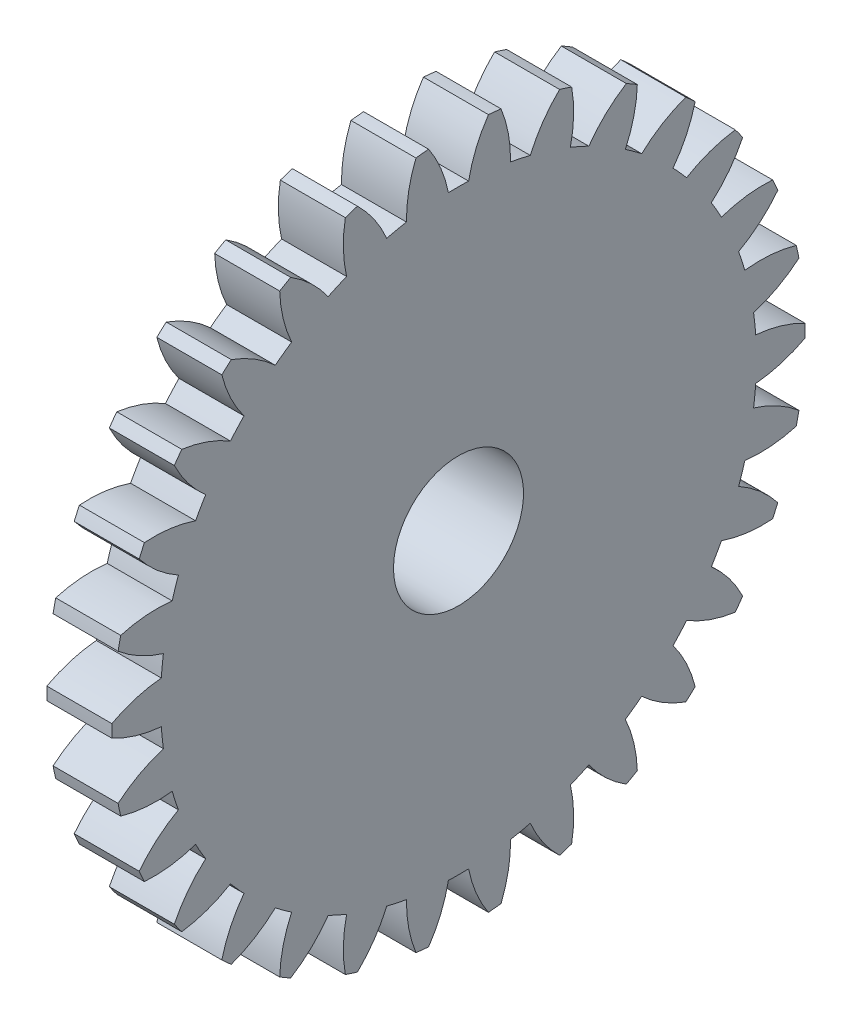
SolidWorks part; units mm, degrees
ref_plane "Plane1" through (0, 0, 0) normal (0, 0, 1) x (1, 0, 0)
ref_plane "Plane2" through (0, 0, 0) normal (0, 1, 0) x (1, 0, 0)
ref_plane "Plane3" through (0, 0, 0) normal (1, 0, 0) x (0, 0, -1)
sketch "HoldingSke" plane through (0, 0, 0) normal (0, 1, 0) x (1, 0, 0)
  line L0 (0, 0) -> (0.866, -0.5)
  line L1 (-15, 0) -> (100, 0) construction
  line L2 (0, 0) -> (-2.1039, 2.3779)
  line L3 (0, 0) -> (-11.863, 4.5341)
  line L4 (0, 0) -> (7.479, 4.318)
  line L5 (0, 0) -> (-5.6217, -2.0967)
  line L6 (0, 0) -> (-2.4869, -1.6779)
  line L7 (-2.1039, 2.3779) -> (-0.8124, 8.2373)
  line L8 (-76.2, 54.61) -> (-75.2, 54.61)
  line L9 (-71.009, 38.7566) -> (-53.1078, 45.2721)
  line L10 (-76.2, 71.12) -> (104.1128, 71.12)
  line L11 (0, 0) -> (-3, 0)
  line L12 (-76.2, 101.6) -> (-76.162, 101.6)
  line L13 (24.9733, 27.94) -> (52.9518, 28.4284)
  line L14 (24.9733, 27.94) -> (24.9743, 27.94)
  line L15 (24.9733, 27.94) -> (100.4006, 29.5858)
  line L16 (-63.627, -1) -> (-12.827, -1)
  circle A0 centre (0, 0) radius 3
  circle A1 centre (0, 0) radius 9
  circle A2 centre (0, 0) radius 9
  circle A3 centre (0, 0) radius 3
  dimension "MHD" = 18
  dimension "Hub_dia" = 18
  dimension "Bore" = 6
  dimension "MBD" = 6
  dimension "Num_teeth" = 30
  dimension "Pitch" = 1
  dimension "Overall_len" = 6
  dimension "Show_teeth" = 30
  dimension "Thickness" = 3
  dimension "OAL" = 6.0001
  dimension "T_dim" = 1
  dimension "Ap" = 20
  dimension "H" = 19.05
  dimension "Pitch_radius" = 180.3128
  dimension "Width" = 3
  dimension "Backlash" = 0.038
  dimension "Addendum_fac" = 1
  dimension "Dedendum_fac" = 1.25
  dimension "Clearance_fac" = 0.25
  dimension "Dedendum_add" = 0.001
  dimension "Module" = 1
sketch "BasProSke" plane through (0, 0, 0) normal (0, 1, 0) x (1, 0, 0)
  line L0 (-10, 0) -> (60, 0) construction
  line L1 (0, 0) -> (0, 16)
  line L2 (0, 0) -> (3, 0)
  line L3 (3, 0) -> (3, 16)
  line L4 (3, 16) -> (0, 16)
  dimension "Thickness" = 3
  dimension "Diameter" = 32
revolve "Base-Revolve" add sketch "BasProSke" angle 360 about L0
sketch "TooCutSke" plane through (0, 0, 0) normal (1, 0, 0) x (0, 0, -1)
  line L1 (0, 0) -> (0, 107) construction
  line L2 (0, 0) -> (-0.8515, 14.9758) construction
  line L3 (0, 0) -> (-3.1323, 29.8014) construction
  line L4 (-0.8515, 14.9758) -> (-1.5661, 14.9007) construction
  arc A0 (0.4664, 13.7411) -> (-0.4664, 13.7411) centre (0, 0) ccw
  arc A1 (1.3975, 15.9644) -> (-1.3975, 15.9644) centre (0, 0) ccw
  circle A2 centre (0, 0) radius 15 construction
  circle A3 centre (0, 0) radius 14.0954 construction
  arc A4 (-0.4664, 13.7411) -> (-1.3975, 15.9644) centre (-6.3534, 12.5823) ccw
  arc A5 (1.3975, 15.9644) -> (0.4664, 13.7411) centre (6.3534, 12.5823) ccw
  dimension "Root_dia" = 27.498
  dimension "Overcut_dia" = 32.0508
  dimension "Pitch_dia" = 30
  dimension "Base_dia" = 28.1908
  dimension "Flank_rad" = 6
  dimension "Half_ang" = 6
  dimension "Half_CT" = 0.7185
extrude "ToothCut" cut sketch "TooCutSke" along normal through all
fillet "Breaks" [suppressed] radius 0.02
fillet "RootFillets" [suppressed] radius 0.251
pattern_circular "TeethCuts" count 30 every 12 about axis through (-10, 0, 0) along (1, 0, 0) of "ToothCut", "RootFillets", "Breaks"
sketch "HubNeaOneSke" plane through (0, 0, 0) normal (-1, 0, 0) x (0, 0, 1)
  circle A0 centre (0, 0) radius 9
  dimension "Diameter" = 18
extrude "HubNearOne" add sketch "HubNeaOneSke" along normal blind 3.0001
sketch "HubNeaBotSke" plane through (0, 0, 0) normal (-1, 0, 0) x (0, 0, 1)
  circle A0 centre (0, 0) radius 9
  dimension "Diameter" = 18
extrude "HubNearBoth" [suppressed] add sketch "HubNeaBotSke" along normal blind 1.5
ref_plane "FarPln" through (3, 0, 0) normal (1, 0, 0) x (0, 0, -1)
sketch "HubFarSke" plane through (3, 0, 0) normal (1, 0, 0) x (0, 0, -1)
  circle A0 centre (0, 0) radius 9
  dimension "Diameter" = 18
extrude "HubFar" [suppressed] add sketch "HubFarSke" along normal blind 1.5
sketch "BorSke" plane through (0, 0, 0) normal (1, 0, 0) x (0, 0, -1)
  circle A0 centre (0, 0) radius 3
  dimension "Diameter" = 6
extrude "Bore" cut sketch "BorSke" along normal mid plane 12.0001
sketch "KeySke" plane through (0, 0, 0) normal (1, 0, 0) x (0, 0, -1)
  line L0 (-1, 0) -> (-1, 4)
  line L1 (-1, 4) -> (1, 4)
  line L2 (1, 4) -> (1, 0)
  line L3 (0, 0) -> (0, 34) construction
  line L4 (-1, 0) -> (1, 0)
  dimension "Offset" = 4
  dimension "Width" = 2
extrude "Keyway" [suppressed] cut sketch "KeySke" along normal mid plane 12.0001
pattern_circular "Keyway2" [suppressed] count 2 every 90 about axis through (-10, 0, 0) along (1, 0, 0)
equation "' \"Module@HoldingSke\" = 6.35"
equation "' \"Num_teeth@HoldingSke\" = 12"
equation "' \"Ap@HoldingSke\" =  20"
equation "' \"Ap@HoldingSke\" = 20"
equation "' \"Width@HoldingSke\" = 0.5 * 25.4"
equation "' \"Hub_dia@HoldingSke\"= 1 * 25.4"
equation "' \"Hub_dia@HoldingSke\" = 1 * 25.4"
equation "' \"Overall_len@HoldingSke\" = 1.0 * 25.4"
equation "' \"Bore@HoldingSke\" = 0.75 * 25.4"
equation "' \"T_dim@HoldingSke\" = 0.1 * 25.4"
equation "' \"Width@KeySke\" = 0.25 * 25.4"
equation "' \"Show_teeth@HoldingSke\" = 13"
equation "' \"Backlash@HoldingSke\" = 0.009 * 25.4"
equation "' \"Addendum_fac@HoldingSke\" = 1.0"
equation "' \"Dedendum_fac@HoldingSke\" = 1.25"
equation "' \"Dedendum_add@HoldingSke\" = 0.00005 * 25.4"
equation "' \"Clearance_fac@HoldingSke\" = 0.25"
equation "\"Pitch@HoldingSke\" = 1 / \"Module@HoldingSke\""
equation "\"Overcut_dia@TooCutSke\" = (\"Num_teeth@HoldingSke\" + 2 * \"Addendum_fac@HoldingSke\") / \"Pitch@HoldingSke\" + 0.002 * 25.4"
equation "\"Pitch_dia@TooCutSke\" = \"Num_teeth@HoldingSke\" / \"Pitch@HoldingSke\""
equation "\"Base_dia@TooCutSke\" = \"Num_teeth@HoldingSke\" / \"Pitch@HoldingSke\" * cos((\"Ap@HoldingSke\"  * 3.14159265 / 180))"
equation "\"Root_dia@TooCutSke\" = (\"Num_teeth@HoldingSke\" + 2) / \"Pitch@HoldingSke\" - 2 * (\"Addendum_fac@HoldingSke\" + \"Dedendum_fac@HoldingSke\") / \"Pitch@HoldingSke\" - \"Dedendum_add@HoldingSke\" * 2"
equation "\"Half_ang@TooCutSke\" = 180 / \"Num_teeth@HoldingSke\""
equation "\"Half_CT@TooCutSke\" = \"Num_teeth@HoldingSke\" / \"Pitch@HoldingSke\" * sin((3.14159265 / 2 / \"Num_teeth@HoldingSke\")) / 2 - 7 * \"Backlash@HoldingSke\" / 4"
equation "\"Flank_rad@TooCutSke\" = \"Num_teeth@HoldingSke\" / \"Pitch@HoldingSke\" / 5"
equation "\"Radius@RootFillets\" = \"Clearance_fac@HoldingSke\" / \"Pitch@HoldingSke\" + \"Dedendum_add@HoldingSke\""
equation "\"Break_rad@Breaks\" = 0.02 / \"Pitch@HoldingSke\""
equation "\"Thickness@HoldingSke\" = \"Width@HoldingSke\""
equation "\"OAL@HoldingSke\" = \"Thickness@HoldingSke\""
equation "\"MHD@HoldingSke\" = (\"Num_teeth@HoldingSke\" + 2) / \"Pitch@HoldingSke\" - 2 * (\"Addendum_fac@HoldingSke\" + \"Dedendum_fac@HoldingSke\")  / \"Pitch@HoldingSke\" - \"Dedendum_add@HoldingSke\" * 2"
equation "\"MBD@HoldingSke\" = (\"Num_teeth@HoldingSke\" + 2) / \"Pitch@HoldingSke\" - 2 * (\"Addendum_fac@HoldingSke\" + \"Dedendum_fac@HoldingSke\")  / \"Pitch@HoldingSke\" - \"Dedendum_add@HoldingSke\" * 2 - 0.002 * 25.4"
equation "\"MHD@HoldingSke\" = ((sgn( \"MHD@HoldingSke\" - \"Hub_dia@HoldingSke\" )-1)*( \"MHD@HoldingSke\" - \"Hub_dia@HoldingSke\" ))/-2+ \"Hub_dia@HoldingSke\""
equation "\"MBD@HoldingSke\" = ((sgn( \"MBD@HoldingSke\" - \"Bore@HoldingSke\" )-1)*( \"MBD@HoldingSke\" - \"Bore@HoldingSke\" ))/-2+ \"Bore@HoldingSke\""
equation "\"OAL@HoldingSke\" = ((sgn( \"OAL@HoldingSke\" - \"Overall_len@HoldingSke\" )+1)*( \"OAL@HoldingSke\" - \"Overall_len@HoldingSke\" ))/2 + \"Overall_len@HoldingSke\" + 0.000002 * 25.4"
equation "\"Num_teeth@TeethCuts\" = int( \"Show_teeth@HoldingSke\" ) + 1"
equation "\"Num_teeth@TeethCuts\" = ((sgn( \"Num_teeth@TeethCuts\" - \"Num_teeth@HoldingSke\" )-1)*( \"Num_teeth@TeethCuts\" - \"Num_teeth@HoldingSke\" ))/-2+ \"Num_teeth@HoldingSke\""
equation "\"Num_teeth@TeethCuts\" = ((sgn( \"Num_teeth@TeethCuts\" - 2.0)+1)*( \"Num_teeth@TeethCuts\" - 2.0))/2 +2.0"
equation "\"Angle@TeethCuts\" = 360.0 / \"Num_teeth@HoldingSke\""
equation "\"Diameter@BasProSke\" = (\"Num_teeth@HoldingSke\" + 2 * \"Addendum_fac@HoldingSke\") / \"Pitch@HoldingSke\""
equation "\"Thickness@BasProSke\"  = \"Thickness@HoldingSke\""
equation "' \"Fillet_rad@BasProSke\" =  \"Thickness@HoldingSke\" * 0.05"
equation "' \"Fillet_rad@BasProSke\" = \"Thickness@HoldingSke\" * 0.05"
equation "\"MHD@HoldingSke\" = ((sgn( \"MHD@HoldingSke\" - \"Root_dia@TooCutSke\" )-1)*( \"MHD@HoldingSke\" - \"Root_dia@TooCutSke\" ))/-2+ \"Root_dia@TooCutSke\""
equation "\"Diameter@HubNeaOneSke\" = \"MHD@HoldingSke\""
equation "\"Length@HubNearOne\" = \"OAL@HoldingSke\" - \"Thickness@BasProSke\""
equation "\"Diameter@HubNeaBotSke\" = \"MHD@HoldingSke\""
equation "\"Length@HubNearBoth\" = ( \"OAL@HoldingSke\" - \"Thickness@BasProSke\" ) / 2.0"
equation "\"Thickness@FarPln\" = \"Thickness@BasProSke\""
equation "\"Diameter@HubFarSke\" = \"MHD@HoldingSke\""
equation "\"Length@HubFar\" = ( \"OAL@HoldingSke\" - \"Thickness@BasProSke\" ) / 2.0"
equation "\"Diameter@BorSke\" = \"MBD@HoldingSke\""
equation "\"D1@Bore\" = \"OAL@HoldingSke\" * 2.0"
equation "\"D1@Keyway\" = \"OAL@HoldingSke\" * 2.0"
equation "\"Offset@KeySke\" = \"T_dim@HoldingSke\" + \"MBD@HoldingSke\" / 2.0"
